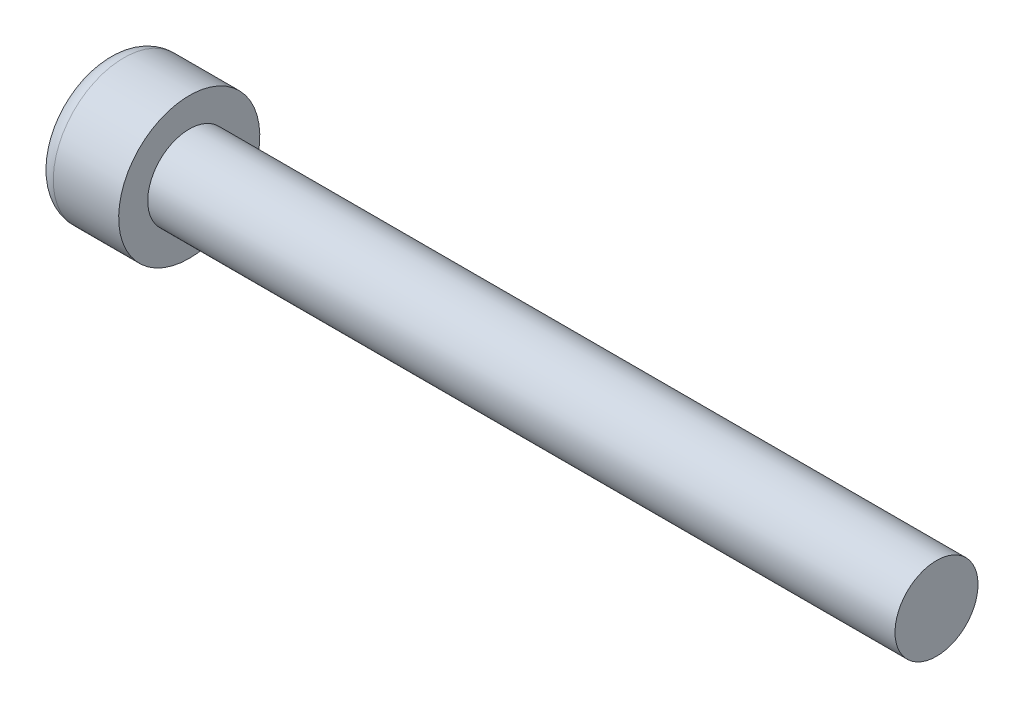
SolidWorks part; units mm, degrees
material "Plain Carbon Steel"
ref_plane "Front Plane" through (0, 0, 0) normal (0, 0, 1) x (1, 0, 0)
ref_plane "Top Plane" through (0, 0, 0) normal (0, 1, 0) x (1, 0, 0)
ref_plane "Right Plane" through (0, 0, 0) normal (1, 0, 0) x (0, 0, -1)
sketch "Sketch1" plane through (0, 0, 0) normal (0, 0, 1) x (1, 0, 0)
  line L0 (0, 0) -> (0, 3.1875)
  line L1 (1.0625, 4.25) -> (5, 4.25)
  line L2 (5, 4.25) -> (5, 2.5)
  line L3 (5, 2.5) -> (50, 2.5)
  line L4 (50, 2.5) -> (50, 0)
  line L5 (50, 0) -> (0, 0) construction
  line L6 (1.0625, 3.1875) -> (1.0625, 2.125) construction
  line L7 (1.0625, 2.125) -> (1.0625, 1.0625) construction
  line L8 (1.0625, 1.0625) -> (1.0625, 0) construction
  line L9 (1.0625, 4.25) -> (1.0625, 3.1875) construction
  line L10 (0, 0) -> (50, 0)
  arc A0 (0, 3.1875) -> (1.0625, 4.25) centre (1.0625, 3.1875) cw
  dimension "D1" = 5
  dimension "D2" = 8.5
  dimension "D3" = 5
  dimension "D4" = 45
revolve "Revolve1" add sketch "Sketch1" angle 360 about L10
sketch "Sketch2" plane through (0, 0, 0) normal (-1, 0, 0) x (0, 0, 1)
  line L1 (0, 2.3094) -> (-2, 1.1547)
  line L2 (-2, 1.1547) -> (-2, -1.1547)
  line L3 (-2, -1.1547) -> (0, -2.3094)
  line L4 (0, -2.3094) -> (2, -1.1547)
  line L5 (2, -1.1547) -> (2, 1.1547)
  line L6 (2, 1.1547) -> (0, 2.3094)
  circle A0 centre (0, 0) radius 2 construction
  dimension "D1" = 4
extrude "Cut-Extrude1" cut sketch "Sketch2" against normal blind 2.5
